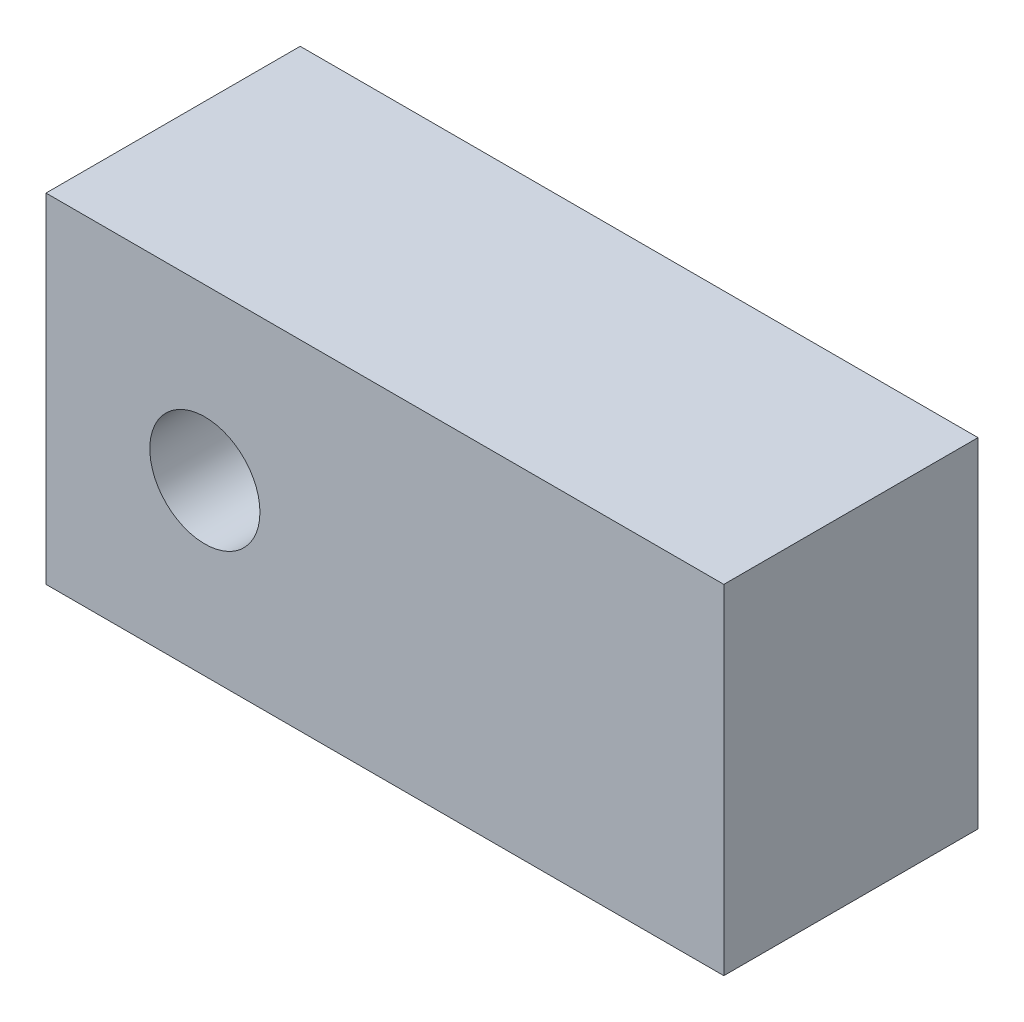
SolidWorks part; units mm, degrees
ref_plane "Front Plane" through (0, 0, 0) normal (0, 0, 1) x (1, 0, 0)
ref_plane "Top Plane" through (0, 0, 0) normal (0, 1, 0) x (1, 0, 0)
ref_plane "Right Plane" through (0, 0, 0) normal (1, 0, 0) x (0, 0, -1)
sketch "Sketch1" plane through (0, 0, 0) normal (0, 0, 1) x (1, 0, 0)
  line L1 (0, 0) -> (20.32, 0)
  line L2 (0, 0) -> (0, 10.16)
  line L3 (0, 10.16) -> (20.32, 10.16)
  line L4 (20.32, 0) -> (20.32, 10.16)
  line L5 (0, 0) -> (20.32, 10.16) construction
  line L6 (0, 10.16) -> (20.32, 0) construction
  point P4 (10.16, 5.08)
  dimension "D1" = 20.32
  dimension "D2" = 10.16
extrude "Boss-Extrude1" add sketch "Sketch1" along normal blind 7.62
sketch "Sketch2" plane through (0, 0, 7.62) normal (0, 0, 1) x (1, 0, 0)
  line L0 (0, 10.16) -> (0, 0) construction
  circle A0 centre (4.7625, 5.08) radius 1.651
  point P4 (0, 0)
  point P5 (0, 5.08)
  point P6 (4.9849, 5.08)
  dimension "D1" = 3.302
  dimension "D2" = 4.7625
extrude "Cut-Extrude1" cut sketch "Sketch2" against normal through all
